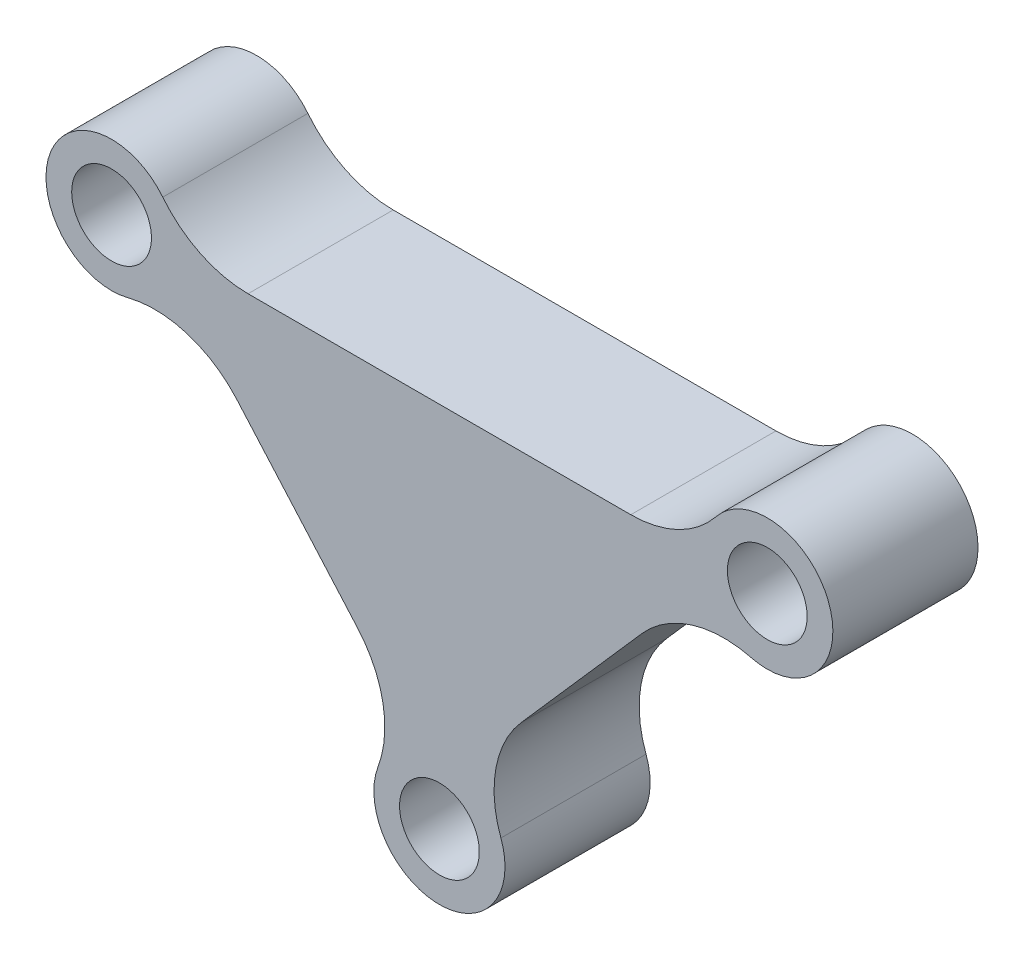
SolidWorks part; units mm, degrees
ref_plane "Plan de face" through (0, 0, 0) normal (0, 0, 1) x (1, 0, 0)
ref_plane "Plan de dessus" through (0, 0, 0) normal (0, 1, 0) x (1, 0, 0)
ref_plane "Plan de droite" through (0, 0, 0) normal (1, 0, 0) x (0, 0, -1)
sketch "Esquisse2" plane through (0, 0, 0) normal (0, 0, 1) x (1, 0, 0)
  line L0 (-13.175, 10) -> (13.175, 10)
  line L1 (13.175, 10) -> (0, -5)
  line L2 (0, -5) -> (-13.175, 10)
  line L3 (0, 0) -> (-13.175, 10) construction
  line L4 (0, 0) -> (13.175, 10) construction
  circle A0 centre (-15, 10) radius 3
  circle A1 centre (-15, 10) radius 1.825
  circle A2 centre (15, 10) radius 3
  circle A3 centre (15, 10) radius 1.825
  circle A4 centre (0, -6.825) radius 3
  circle A5 centre (0, -6.825) radius 1.825
  dimension "D2" = 3.65
  dimension "D3" = 6
  dimension "D1" = 5
  dimension "D4" = 10
  dimension "D5" = 15
extrude "Boss.-Extru.1" add sketch "Esquisse2" along normal blind 6.64 contours A4 L1 A2 L0 A0 L2 | L1 A5 L2 A4 | L1 A4 L2 | A3 | A1
fillet "Congé1" radius 5 6 edges at (-12, 10, 3.32) (-12.2089, 8.9001, 3.32) (-0.9084, -3.9658, 3.32) (12.2089, 8.9001, 3.32) (12, 10, 3.32) (0.9084, -3.9658, 3.32)
